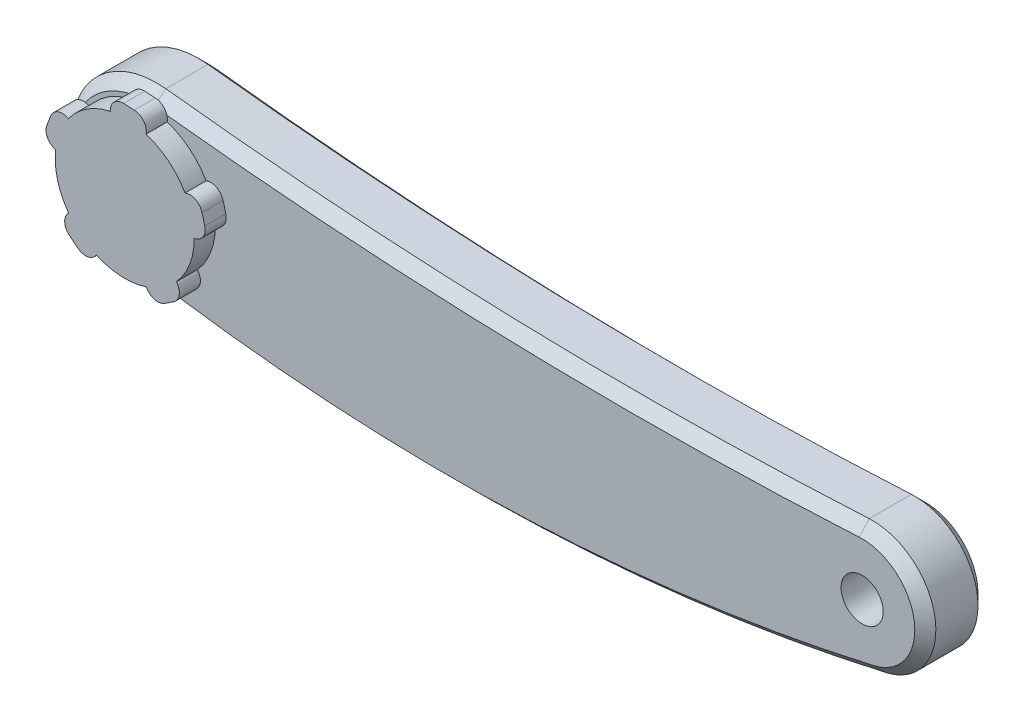
SolidWorks part; units mm, degrees
ref_plane "Front Plane" through (0, 0, 0) normal (0, 0, 1) x (1, 0, 0)
ref_plane "Top Plane" through (0, 0, 0) normal (0, 1, 0) x (1, 0, 0)
ref_plane "Right Plane" through (0, 0, 0) normal (1, 0, 0) x (0, 0, -1)
sketch "Sketch1" plane through (0, 0, 0) normal (0, 0, 1) x (1, 0, 0)
  line L0 (0, 0) -> (170, 0) construction
  circle A0 centre (0, 0) radius 20
  circle A1 centre (170, 0) radius 15
  arc A2 (2.2535, 19.8726) -> (169.1861, 14.9779) centre (114.9265, 1013.5048) ccw
  arc A3 (-3.3618, -19.7154) -> (173.3697, -14.6166) centre (72.2794, 423.8817) ccw
  dimension "D2" = 40
  dimension "D3" = 30
  dimension "D4" = 1000
  dimension "D5" = 450
  dimension "D1" = 170
extrude "Boss-Extrude1" add sketch "Sketch1" along normal mid plane 15
chamfer "Chamfer1" distance 2.5 angle 45 8 edges at (184.8523, 2.0996, -7.5) (85.6174, 13.9344, -7.5) (-19.8018, 2.8087, -7.5) (85.2568, -25.9311, -7.5) (-19.8018, 2.8087, 7.5) (85.6174, 13.9344, 7.5) (184.8523, 2.0996, 7.5) (85.2568, -25.9311, 7.5)
sketch "Sketch2" plane through (0, 0, 7.5) normal (0, 0, 1) x (1, 0, 0)
  circle A0 centre (0, 0) radius 16.5
  dimension "D1" = 33
extrude "Boss-Extrude2" add sketch "Sketch2" along normal blind 5
sketch "Sketch3" plane through (0, 0, 12.5) normal (0, 0, 1) x (1, 0, 0)
  line L0 (0, 0) -> (16.0903, 0)
  line L1 (18.9881, 3.7765) -> (18.3324, 6.2235)
  line L2 (13.9346, 8.0452) -> (0, 0)
  line L3 (0, 0) -> (18.6603, 5) construction
  line L4 (11.9574, -10.7665) -> (0, 0)
  line L5 (0, 0) -> (4.9722, -15.3028)
  line L6 (9.4593, -16.8918) -> (11.584, -15.512)
  line L7 (-6.5445, -14.6992) -> (0, 0)
  line L8 (0, 0) -> (-13.0173, -9.4577)
  line L9 (-13.142, -14.2161) -> (-11.1731, -15.8105)
  line L10 (-16.0022, 1.6819) -> (0, 0)
  line L11 (0, 0) -> (-13.0173, 9.4577)
  line L12 (-17.5814, 8.1057) -> (-18.4893, 5.7406)
  line L13 (-3.3454, 15.7387) -> (0, 0)
  line L14 (0, 0) -> (4.9722, 15.3028)
  line L15 (2.276, 19.2257) -> (-0.2539, 19.3583)
  arc A0 (16.0903, 0) -> (18.9881, 3.7765) centre (16.0903, 3) ccw
  arc A1 (18.3324, 6.2235) -> (13.9346, 8.0452) centre (15.4346, 5.4471) ccw
  arc A2 (11.584, -15.512) -> (11.9574, -10.7665) centre (9.95, -12.996) ccw
  arc A3 (4.9722, -15.3028) -> (9.4593, -16.8918) centre (7.8254, -14.3758) ccw
  arc A4 (-11.1731, -15.8105) -> (-6.5445, -14.6992) centre (-9.2852, -13.479) ccw
  arc A5 (-13.0173, -9.4577) -> (-13.142, -14.2161) centre (-11.254, -11.8847) ccw
  arc A6 (-18.4893, 5.7406) -> (-16.0022, 1.6819) centre (-15.6886, 4.6655) ccw
  arc A7 (-13.0173, 9.4577) -> (-17.5814, 8.1057) centre (-14.7807, 7.0306) ccw
  arc A8 (-0.2539, 19.3583) -> (-3.3454, 15.7387) centre (-0.4109, 16.3624) ccw
  arc A9 (4.9722, 15.3028) -> (2.276, 19.2257) centre (2.119, 16.2299) ccw
  point P10 (17.3205, 10)
  point P37 (0, 0)
  circle M12 centre (0, 0) radius 16.5
  dimension "D3" = 3
  dimension "D1" = 20
  dimension "D2" = 30
  dimension "D4" = 5
extrude "Boss-Extrude3" add sketch "Sketch3" against normal blind 5 contours A9 L15 A8 M12 | L3 L1 A1 M12 | L3 A0 L1 M12 | A3 L6 A2 M12 | A5 L9 A4 M12 | L11 A7 L12 A6 L10
sketch "Sketch4" plane through (0, 0, 7.5) normal (0, 0, 1) x (1, 0, 0)
  circle A0 centre (170, 0) radius 5
extrude "Cut-Extrude1" cut sketch "Sketch4" against normal blind 10
sketch "Sketch5" plane through (0, 0, -7.5) normal (0, 0, -1) x (-1, 0, 0)
  circle A0 centre (0, 0) radius 5
extrude "Boss-Extrude4" add sketch "Sketch5" along normal blind 10
